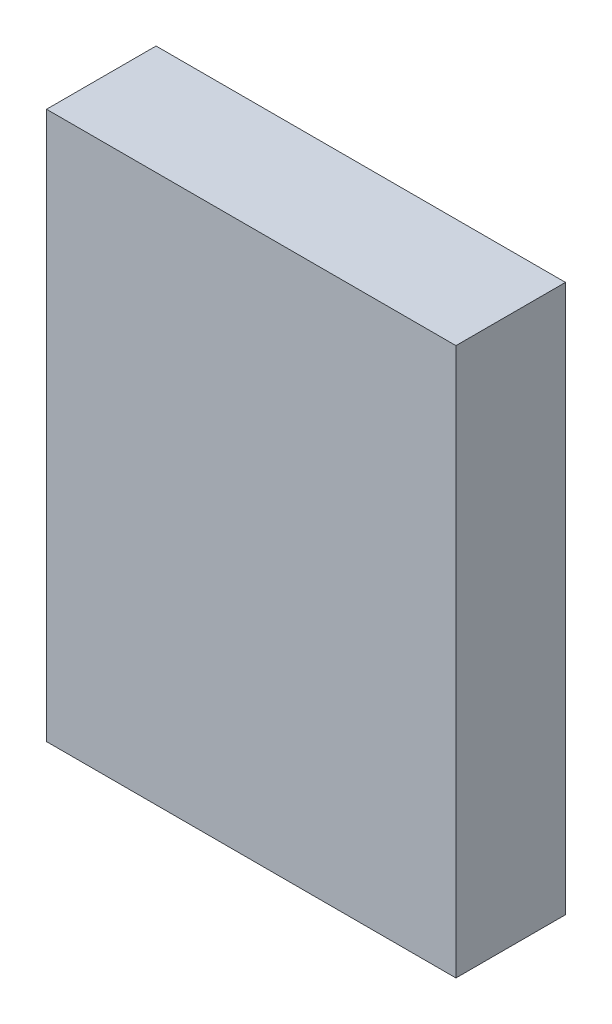
SolidWorks part; units mm, degrees
ref_plane "Спереди" through (0, 0, 0) normal (0, 0, 1) x (1, 0, 0)
ref_plane "Сверху" through (0, 0, 0) normal (0, 1, 0) x (1, 0, 0)
ref_plane "Справа" through (0, 0, 0) normal (1, 0, 0) x (0, 0, -1)
sketch "Эскиз5" plane through (0, 0, 0) normal (0, 0, 1) x (1, 0, 0)
  line L1 (-18.689, -25) -> (18.689, -25)
  line L2 (-18.689, -25) -> (-18.689, 25)
  line L3 (-18.689, 25) -> (18.689, 25)
  line L4 (18.689, -25) -> (18.689, 25)
  line L5 (-18.689, -25) -> (18.689, 25) construction
  line L6 (-18.689, 25) -> (18.689, -25) construction
  point P0 (0, 0)
extrude "Бобышка-Вытянуть2" add sketch "Эскиз5" along normal blind 10 contours L2 L3 L4 L1
sketch "Эскиз6" plane through (0, 0, 10) normal (0, 0, 1) x (1, 0, 0)
  circle A0 centre (0, 0) radius 15
sketch "Перлаж круг" plane through (0, 0, 10) normal (0, 0, 1) x (1, 0, 0)
  circle A50 centre (-5.5355, -11.7226) radius 1.48
  circle A51 centre (-7.0486, -10.8802) radius 1.48
  circle A52 centre (-8.4359, -9.8436) radius 1.48
  circle A53 centre (-9.6727, -8.6314) radius 1.48
  circle A54 centre (-10.7368, -7.2651) radius 1.48
  circle A55 centre (-11.6093, -5.7692) radius 1.48
  circle A56 centre (-12.2747, -4.1704) radius 1.48
  circle A57 centre (-12.7211, -2.4971) radius 1.48
  circle A58 centre (-12.9404, -0.7793) radius 1.48
  circle A59 centre (-12.9288, 0.9525) radius 1.48
  circle A60 centre (-12.6865, 2.6672) radius 1.48
  circle A61 centre (-12.2178, 4.3343) radius 1.48
  circle A62 centre (-11.5311, 5.9241) radius 1.48
  circle A63 centre (-10.6386, 7.4082) radius 1.48
  circle A64 centre (-9.5562, 8.7601) radius 1.48
  circle A65 centre (-8.3034, 9.9557) radius 1.48
  circle A66 centre (-6.9023, 10.9736) radius 1.48
  circle A67 centre (-5.3781, 11.7956) radius 1.48
  circle A68 centre (-3.7579, 12.4072) radius 1.48
  circle A69 centre (-2.0706, 12.7974) radius 1.48
  circle A70 centre (-0.3464, 12.9592) radius 1.48
  circle A71 centre (1.3839, 12.8898) radius 1.48
  circle A72 centre (3.0896, 12.5903) radius 1.48
  circle A73 centre (4.7402, 12.0661) radius 1.48
  circle A74 centre (6.3061, 11.3267) radius 1.48
  circle A75 centre (7.7596, 10.3851) radius 1.48
  circle A76 centre (9.0745, 9.2582) radius 1.48
  circle A77 centre (10.2276, 7.9661) radius 1.48
  circle A78 centre (11.1981, 6.5318) radius 1.48
  circle A79 centre (11.9688, 4.9809) radius 1.48
  circle A80 centre (12.5259, 3.3412) radius 1.48
  circle A81 centre (12.8594, 1.6419) radius 1.48
  circle A82 centre (12.9635, -0.0868) radius 1.48
  circle A83 centre (12.8363, -1.8139) radius 1.48
  circle A84 centre (12.48, -3.5086) radius 1.48
  circle A85 centre (11.901, -5.1407) radius 1.48
  circle A86 centre (11.1096, -6.6811) radius 1.48
  circle A87 centre (10.12, -8.1023) radius 1.48
  circle A88 centre (8.9498, -9.3788) radius 1.48
  circle A89 centre (7.6198, -10.488) radius 1.48
  circle A90 centre (-3.817, -10.2437) radius 1.48
  circle A91 centre (-5.3724, -9.5205) radius 1.48
  circle A92 centre (-6.7956, -8.5628) radius 1.48
  circle A93 centre (-8.0515, -7.3943) radius 1.48
  circle A94 centre (-9.1091, -6.0438) radius 1.48
  circle A95 centre (-9.9424, -4.5444) radius 1.48
  circle A96 centre (-10.5309, -2.9331) radius 1.48
  circle A97 centre (-10.8601, -1.2496) radius 1.48
  circle A98 centre (-10.9219, 0.4647) radius 1.48
  circle A99 centre (-10.7147, 2.1675) radius 1.48
  circle A100 centre (-10.2437, 3.817) radius 1.48
  circle A101 centre (-9.5205, 5.3724) radius 1.48
  circle A102 centre (-8.5628, 6.7956) radius 1.48
  circle A103 centre (-7.3943, 8.0515) radius 1.48
  circle A104 centre (-6.0438, 9.1091) radius 1.48
  circle A105 centre (-4.5444, 9.9424) radius 1.48
  circle A106 centre (-2.9331, 10.5309) radius 1.48
  circle A107 centre (-1.2496, 10.8601) radius 1.48
  circle A108 centre (0.4647, 10.9219) radius 1.48
  circle A109 centre (2.1675, 10.7147) radius 1.48
  circle A110 centre (3.817, 10.2437) radius 1.48
  circle A111 centre (5.3724, 9.5205) radius 1.48
  circle A112 centre (6.7956, 8.5628) radius 1.48
  circle A113 centre (8.0515, 7.3943) radius 1.48
  circle A114 centre (9.1091, 6.0438) radius 1.48
  circle A115 centre (9.9424, 4.5444) radius 1.48
  circle A116 centre (10.5309, 2.9331) radius 1.48
  circle A117 centre (10.8601, 1.2496) radius 1.48
  circle A118 centre (10.9219, -0.4647) radius 1.48
  circle A119 centre (10.7147, -2.1675) radius 1.48
  circle A120 centre (10.2437, -3.817) radius 1.48
  circle A121 centre (9.5205, -5.3724) radius 1.48
  circle A122 centre (8.5628, -6.7956) radius 1.48
  circle A123 centre (7.3943, -8.0515) radius 1.48
  circle A124 centre (-2.2586, -8.6536) radius 1.48
  circle A125 centre (-3.8554, -8.0698) radius 1.48
  circle A126 centre (-5.313, -7.1943) radius 1.48
  circle A127 centre (-6.5785, -6.0588) radius 1.48
  circle A128 centre (-7.6063, -4.7043) radius 1.48
  circle A129 centre (-8.3591, -3.1798) radius 1.48
  circle A130 centre (-8.8099, -1.5404) radius 1.48
  circle A131 centre (-8.9422, 0.1547) radius 1.48
  circle A132 centre (-8.7513, 1.8442) radius 1.48
  circle A133 centre (-8.2441, 3.4671) radius 1.48
  circle A134 centre (-7.439, 4.9647) radius 1.48
  circle A135 centre (-6.365, 6.2828) radius 1.48
  circle A136 centre (-5.0609, 7.3738) radius 1.48
  circle A137 centre (-3.574, 8.1984) radius 1.48
  circle A138 centre (-1.9578, 8.7266) radius 1.48
  circle A139 centre (-0.2709, 8.9394) radius 1.48
  circle A140 centre (1.4257, 8.8291) radius 1.48
  circle A141 centre (3.0709, 8.3998) radius 1.48
  circle A142 centre (4.6051, 7.6668) radius 1.48
  circle A143 centre (5.9728, 6.6567) radius 1.48
  circle A144 centre (7.1247, 5.4061) radius 1.48
  circle A145 centre (8.019, 3.96) radius 1.48
  circle A146 centre (8.6235, 2.3709) radius 1.48
  circle A147 centre (8.9164, 0.696) radius 1.48
  circle A148 centre (8.887, -1.004) radius 1.48
  circle A149 centre (8.5364, -2.6678) radius 1.48
  circle A150 centre (7.8772, -4.2351) radius 1.48
  circle A151 centre (6.9334, -5.6493) radius 1.48
  circle A152 centre (-3.1508, -6.0227) radius 1.48
  circle A153 centre (-4.5496, -5.0499) radius 1.48
  circle A154 centre (-5.6625, -3.7598) radius 1.48
  circle A155 centre (-6.4197, -2.2335) radius 1.48
  circle A156 centre (-6.7734, -0.5668) radius 1.48
  circle A157 centre (-6.7016, 1.1355) radius 1.48
  circle A158 centre (-6.2086, 2.7664) radius 1.48
  circle A159 centre (-5.3256, 4.2236) radius 1.48
  circle A160 centre (-4.1079, 5.4153) radius 1.48
  circle A161 centre (-2.6321, 6.2668) radius 1.48
  circle A162 centre (-0.991, 6.7245) radius 1.48
  circle A163 centre (0.7125, 6.7596) radius 1.48
  circle A164 centre (2.3711, 6.3701) radius 1.48
  circle A165 centre (3.8808, 5.5803) radius 1.48
  circle A166 centre (5.1467, 4.4399) radius 1.48
  circle A167 centre (6.0891, 3.0204) radius 1.48
  circle A168 centre (6.649, 1.4113) radius 1.48
  circle A169 centre (6.791, -0.2866) radius 1.48
  circle A170 centre (6.5064, -1.9665) radius 1.48
  circle A171 centre (5.813, -3.5228) radius 1.48
  circle A172 centre (-3.4358, -3.2912) radius 1.48
  circle A173 centre (-4.3927, -1.8278) radius 1.48
  circle A174 centre (-4.7563, -0.1176) radius 1.48
  circle A175 centre (-4.4776, 1.6085) radius 1.48
  circle A176 centre (-3.5942, 3.1174) radius 1.48
  circle A177 centre (-2.2253, 4.2053) radius 1.48
  circle A178 centre (-0.5559, 4.7252) radius 1.48
  circle A179 centre (1.1885, 4.6069) radius 1.48
  circle A180 centre (2.7725, 3.8665) radius 1.48
  circle A181 centre (3.982, 2.6038) radius 1.48
  circle A182 centre (4.6537, 0.9895) radius 1.48
  circle A183 centre (4.6969, -0.7584) radius 1.48
  circle A184 centre (4.1058, -2.4039) radius 1.48
  circle A185 centre (-3.0073, -0.5497) radius 1.48
  circle A186 centre (-2.756, 1.3229) radius 1.48
  circle A187 centre (-1.4521, 2.6902) radius 1.48
  circle A188 centre (0.4065, 3.0299) radius 1.48
  circle A189 centre (2.1098, 2.2123) radius 1.48
  circle A190 centre (3.0073, 0.5497) radius 1.48
  circle A191 centre (2.756, -1.3229) radius 1.48
  circle A196 centre (6.1539, -11.4101) radius 1.48
  circle A197 centre (4.5782, -12.1285) radius 1.48
  circle A198 centre (2.9208, -12.6305) radius 1.48
  circle A199 centre (1.2113, -12.9071) radius 1.48
  circle A200 centre (-0.5199, -12.9534) radius 1.48
  circle A201 centre (-2.2418, -12.7685) radius 1.48
  circle A202 centre (-3.9237, -12.3558) radius 1.48
  circle A203 centre (6.0438, -9.1091) radius 1.48
  circle A204 centre (4.5444, -9.9424) radius 1.48
  circle A205 centre (2.9331, -10.5309) radius 1.48
  circle A206 centre (1.2496, -10.8601) radius 1.48
  circle A207 centre (-0.4647, -10.9219) radius 1.48
  circle A208 centre (-2.1675, -10.7147) radius 1.48
  circle A209 centre (5.739, -6.8594) radius 1.48
  circle A210 centre (4.3371, -7.8215) radius 1.48
  circle A211 centre (2.7785, -8.501) radius 1.48
  circle A212 centre (1.1195, -8.8732) radius 1.48
  circle A213 centre (-0.58, -8.9247) radius 1.48
  circle A216 centre (4.7543, -4.8577) radius 1.48
  circle A217 centre (3.3968, -5.8874) radius 1.48
  circle A218 centre (1.826, -6.5472) radius 1.48
  circle A219 centre (0.1404, -6.7956) radius 1.48
  circle A220 centre (-1.5541, -6.617) radius 1.48
  circle A226 centre (2.9601, -3.7248) radius 1.48
  circle A227 centre (1.4147, -4.5426) radius 1.48
  circle A228 centre (-0.3218, -4.7469) radius 1.48
  circle A229 centre (-2.0148, -4.3101) radius 1.48
  circle A231 centre (1.4521, -2.6902) radius 1.48
  circle A232 centre (-0.4065, -3.0299) radius 1.48
  circle A233 centre (-2.1098, -2.2123) radius 1.48
  point P103 (0, 0)
  point P184 (0, 0)
  point P252 (0, 0)
  point P310 (0, 0)
  point P351 (0, 0)
  point P378 (0, 0)
  point P393 (0, 0)
  point P402 (0, 0)
  dimension "D2" = 47
  dimension "D3" = 40
  dimension "D4" = 33
  dimension "D5" = 25
  dimension "D6" = 17
  dimension "D7" = 10
sketch "подточка" plane through (0, 0, 10) normal (0, 0, 1) x (1, 0, 0)
  circle A0 centre (-15.0549, 21.3795) radius 1.48
  circle A1 centre (-5.0549, 21.3795) radius 1.48
  circle A2 centre (4.9451, 21.3795) radius 1.48
  circle A3 centre (14.9451, 21.3795) radius 1.48
  dimension "D1" = 4
